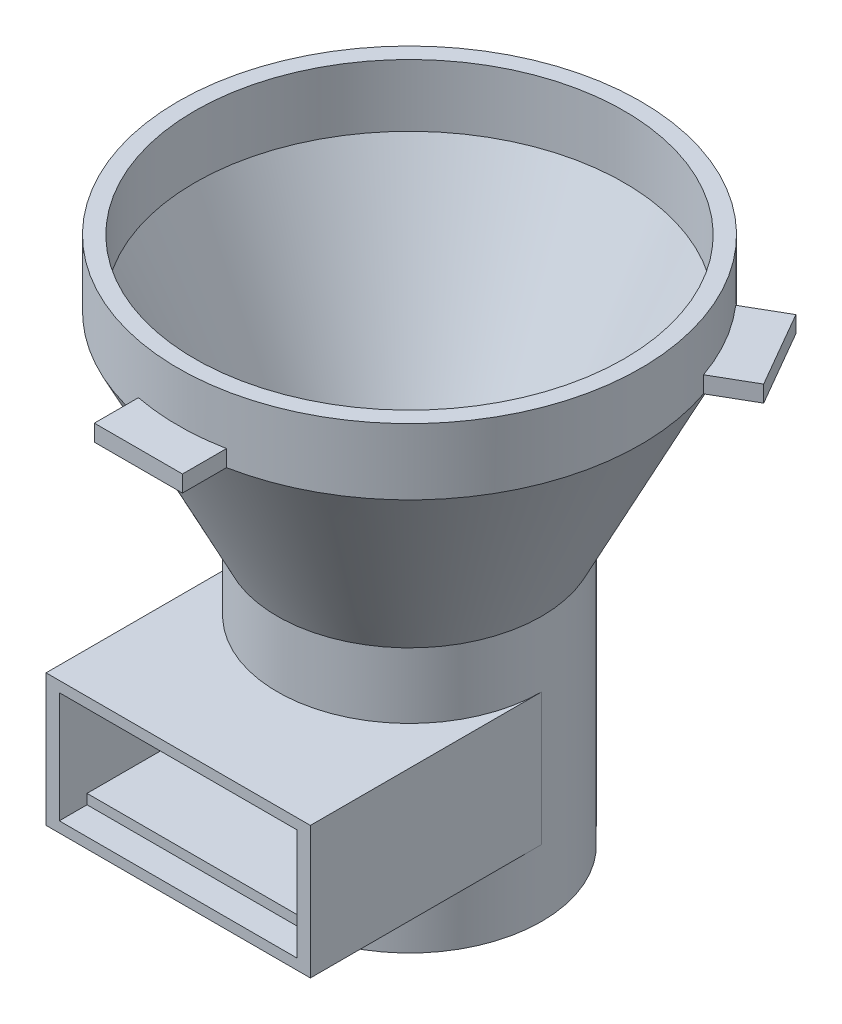
SolidWorks part; units mm, degrees
ref_plane "Front Plane" through (0, 0, 0) normal (0, 0, 1) x (1, 0, 0)
ref_plane "Top Plane" through (0, 0, 0) normal (0, 1, 0) x (1, 0, 0)
ref_plane "Right Plane" through (0, 0, 0) normal (1, 0, 0) x (0, 0, -1)
sketch "Sketch1" plane through (0, 0, 0) normal (0, 0, 1) x (1, 0, 0)
  line L0 (0, 0) -> (0, 92.075) construction
  line L1 (0, 92.075) -> (-44.45, 92.075)
  line L2 (-44.45, 92.075) -> (-44.45, 88.9)
  line L3 (-44.45, 88.9) -> (-25.4, 50.8)
  line L4 (-25.4, 50.8) -> (-25.4, 0)
  line L5 (-25.4, 0) -> (0, 0)
  line L6 (0, 0) -> (0, 92.075)
  dimension "D1" = 3.175
  dimension "D2" = 38.1
  dimension "D3" = 44.45
  dimension "D4" = 50.8
  dimension "D5" = 25.4
revolve "Revolve1" add sketch "Sketch1" angle 360 about L0
shell "Shell1" thickness 3.175
sketch "Sketch2" plane through (0, 92.075, 0) normal (0, 1, 0) x (1, 0, 0)
  line L1 (0, -52.1029) -> (-8.4667, -52.1029)
  line L2 (-8.4667, -52.1029) -> (-8.4667, -43.6362)
  line L3 (0, -52.1029) -> (8.4667, -52.1029)
  line L4 (8.4667, -52.1029) -> (8.4667, -43.6362)
  circle A0 centre (0, 0) radius 44.45 construction
  arc A1 (-8.4667, -43.6362) -> (8.4667, -43.6362) centre (0, 0) ccw
  dimension "D1" = 16.9333
  dimension "D2" = 8.4667
extrude "Boss-Extrude1" add sketch "Sketch2" against normal blind 3.175
pattern_circular "CirPattern1" count 3 every 120 about axis through (0, 0, 0) along (0, 1, 0) of "Boss-Extrude1"
sketch "Sketch4" plane through (0, 0, 0) normal (0, 0, 1) x (1, 0, 0)
  line L0 (-25.4, 50.8) -> (-25.4, 0) construction
  line L1 (-25.4, 38.2205) -> (25.4, 38.2205)
  line L2 (-25.4, 38.2205) -> (-25.4, 12.8205)
  line L3 (-25.4, 12.8205) -> (25.4, 12.8205)
  line L4 (25.4, 38.2205) -> (25.4, 12.8205)
  line L5 (25.4, 0) -> (25.4, 50.8) construction
  dimension "D1" = 25.4
extrude "Boss-Extrude2" add sketch "Sketch4" along normal blind 44.45
sketch "Sketch5" plane through (0, 38.2205, 0) normal (0, 1, 0) x (1, 0, 0)
  circle A0 centre (0, 0) radius 22.225
extrude "Cut-Extrude1" cut sketch "Sketch5" against normal through all both and the other way through all
sketch "Sketch6" plane through (0, 0, 44.45) normal (0, 0, 1) x (1, 0, 0)
  line L0 (0, 12.8205) -> (0, 38.2205) construction
  line L1 (-25.4, 12.8205) -> (25.4, 12.8205) construction
  line L2 (25.4, 38.2205) -> (-25.4, 38.2205) construction
  line L4 (-22.86, 14.8525) -> (22.86, 14.8525)
  line L5 (-22.86, 14.8525) -> (-22.86, 36.1885)
  line L6 (-22.86, 36.1885) -> (22.86, 36.1885)
  line L7 (22.86, 14.8525) -> (22.86, 36.1885)
  line L8 (-22.86, 14.8525) -> (22.86, 36.1885) construction
  line L9 (-22.86, 36.1885) -> (22.86, 14.8525) construction
  point P6 (0, 25.5205)
  dimension "D1" = 21.336
  dimension "D2" = 45.72
extrude "Cut-Extrude2" cut sketch "Sketch6" against normal blind 40.767
sketch "Sketch7" plane through (0, 14.8525, 0) normal (0, 1, 0) x (1, 0, 0)
  line L0 (0, -22.8604) -> (-22.86, -22.8604)
  line L2 (-22.86, -3.683) -> (-22.86, -44.45) construction
  line L3 (-22.86, -22.8604) -> (-22.8604, 0)
  line L4 (0, -22.8604) -> (22.86, -22.8604)
  line L5 (22.86, -3.683) -> (22.86, -44.45) construction
  line L6 (22.86, -22.8604) -> (22.8604, 0)
  line L7 (-22.8604, 0) -> (-22.225, 0)
  line L8 (21.9177, -3.683) -> (22.86, -3.683)
  line L9 (22.86, -3.683) -> (22.8604, 0)
  arc A2 (-22.225, 0) -> (21.9177, -3.683) centre (0, 0) ccw
  arc A3 (-21.9177, -3.683) -> (21.9177, -3.683) centre (0, 0) ccw construction
extrude "Boss-Extrude3" add sketch "Sketch7" along normal blind 1.905
sketch "Sketch8" plane through (0, 0, 22.8604) normal (0, 0, 1) x (1, 0, 0)
  line L1 (-22.86, 16.7575) -> (22.86, 16.7575)
  line L2 (-22.86, 16.7575) -> (-22.86, 14.8525)
  line L3 (-22.86, 14.8525) -> (22.86, 14.8525)
  line L4 (22.86, 16.7575) -> (22.86, 14.8525)
extrude "Boss-Extrude4" add sketch "Sketch8" along normal blind 16.256
sketch "Sketch10" plane through (0, 92.075, 0) normal (0, 1, 0) x (1, 0, 0)
  circle A0 centre (0, 0) radius 44.45
  arc A2 (-42.0234, 14.4858) -> (-8.4667, -43.6362) centre (0, 0) ccw construction
  circle A4 centre (0, 0) radius 41.275
extrude "Boss-Extrude5" add sketch "Sketch10" along normal blind 9.525
